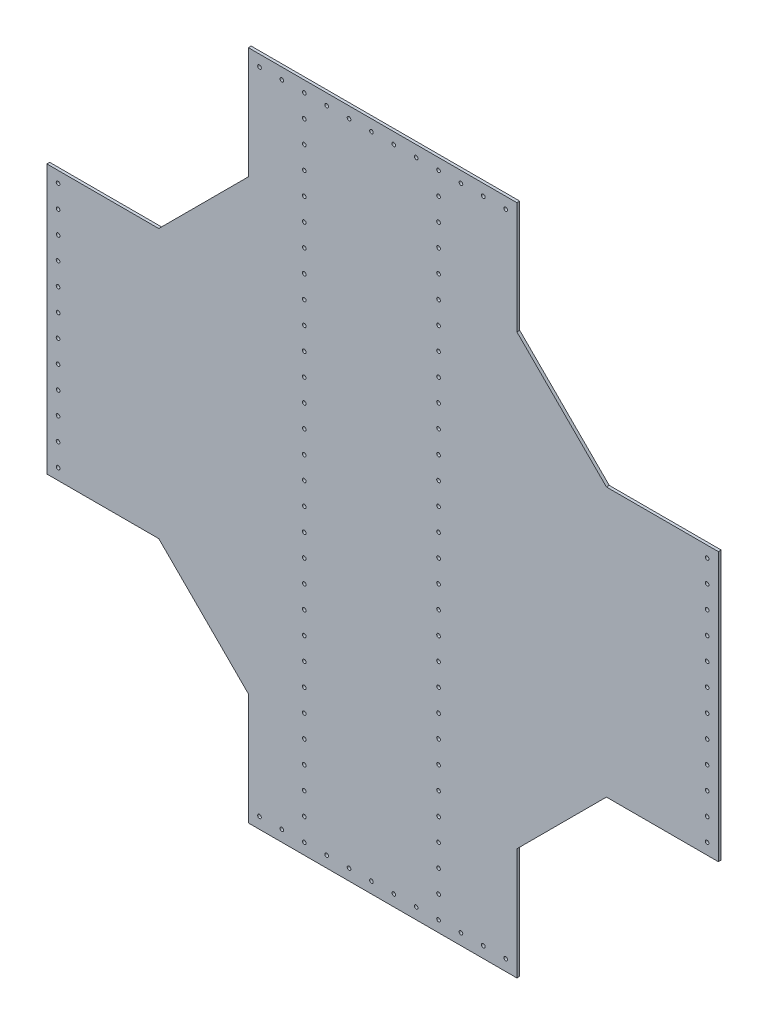
SolidWorks part; units mm, degrees
ref_plane "Front Plane" through (0, 0, 0) normal (0, 0, 1) x (1, 0, 0)
ref_plane "Top Plane" through (0, 0, 0) normal (0, 1, 0) x (1, 0, 0)
ref_plane "Right Plane" through (0, 0, 0) normal (1, 0, 0) x (0, 0, -1)
sketch "Sketch1" plane through (0, 0, 0) normal (0, 0, 1) x (1, 0, 0)
  line L0 (317.5, 38.1) -> (317.5, 749.3) construction
  line L1 (317.5, 546.1) -> (190.5, 546.1)
  line L2 (317.5, 546.1) -> (317.5, 241.3)
  line L3 (317.5, 241.3) -> (190.5, 241.3)
  line L4 (-444.5, 546.1) -> (-444.5, 241.3)
  line L5 (-444.5, 38.1) -> (-444.5, 749.3) construction
  line L7 (88.9, 774.7) -> (-215.9, 774.7)
  line L8 (88.9, 774.7) -> (88.9, 647.7)
  line L9 (88.9, 12.7) -> (-215.9, 12.7)
  line L10 (-215.9, 774.7) -> (-215.9, 647.7)
  line L11 (317.5, 12.7) -> (-444.5, 12.7) construction
  line L12 (190.5, 241.3) -> (88.9, 139.7)
  line L13 (317.5, 774.7) -> (-444.5, 774.7) construction
  line L14 (-63.5, 774.7) -> (-63.5, 12.7) construction
  line L15 (317.5, 393.7) -> (-444.5, 393.7) construction
  line L16 (190.5, 546.1) -> (88.9, 647.7)
  line L17 (-317.5, 241.3) -> (-215.9, 139.7)
  line L18 (-317.5, 546.1) -> (-215.9, 647.7)
  line L19 (88.9, 139.7) -> (88.9, 12.7)
  line L20 (-317.5, 546.1) -> (-444.5, 546.1)
  line L21 (-215.9, 139.7) -> (-215.9, 12.7)
  line L22 (-317.5, 241.3) -> (-444.5, 241.3)
  line L23 (76.2, 762) -> (50.8, 762) construction
  line L24 (-152.4, 25.4) -> (-152.4, 50.8) construction
  line L25 (0, 25.4) -> (0, 50.8) construction
  line L26 (-431.8, 533.4) -> (-431.8, 508) construction
  circle A0 centre (76.2, 762) radius 2.0701
  circle A1 centre (50.8, 762) radius 2.0701
  circle A2 centre (25.4, 762) radius 2.0701
  circle A3 centre (0, 762) radius 2.0701
  circle A4 centre (-25.4, 762) radius 2.0701
  circle A5 centre (-50.8, 762) radius 2.0701
  circle A6 centre (-76.2, 762) radius 2.0701
  circle A7 centre (-101.6, 762) radius 2.0701
  circle A8 centre (-127, 762) radius 2.0701
  circle A9 centre (-152.4, 762) radius 2.0701
  circle A10 centre (-177.8, 762) radius 2.0701
  circle A11 centre (-203.2, 762) radius 2.0701
  circle A12 centre (76.2, 25.4) radius 2.0701
  circle A13 centre (50.8, 25.4) radius 2.0701
  circle A14 centre (-50.8, 25.4) radius 2.0701
  circle A15 centre (-25.4, 25.4) radius 2.0701
  circle A16 centre (0, 25.4) radius 2.0701
  circle A17 centre (25.4, 25.4) radius 2.0701
  circle A18 centre (-76.2, 25.4) radius 2.0701
  circle A19 centre (-101.6, 25.4) radius 2.0701
  circle A20 centre (-127, 25.4) radius 2.0701
  circle A21 centre (-152.4, 25.4) radius 2.0701
  circle A22 centre (-177.8, 25.4) radius 2.0701
  circle A23 centre (-203.2, 25.4) radius 2.0701
  circle A24 centre (-152.4, 50.8) radius 2.0701
  circle A25 centre (-152.4, 76.2) radius 2.0701
  circle A26 centre (-152.4, 101.6) radius 2.0701
  circle A27 centre (-152.4, 127) radius 2.0701
  circle A28 centre (-152.4, 152.4) radius 2.0701
  circle A29 centre (-152.4, 177.8) radius 2.0701
  circle A30 centre (-152.4, 203.2) radius 2.0701
  circle A31 centre (-152.4, 228.6) radius 2.0701
  circle A32 centre (-152.4, 254) radius 2.0701
  circle A33 centre (-152.4, 279.4) radius 2.0701
  circle A34 centre (-152.4, 304.8) radius 2.0701
  circle A35 centre (-152.4, 330.2) radius 2.0701
  circle A36 centre (-152.4, 355.6) radius 2.0701
  circle A37 centre (-152.4, 381) radius 2.0701
  circle A38 centre (-152.4, 406.4) radius 2.0701
  circle A39 centre (-152.4, 431.8) radius 2.0701
  circle A40 centre (-152.4, 457.2) radius 2.0701
  circle A41 centre (-152.4, 482.6) radius 2.0701
  circle A42 centre (-152.4, 508) radius 2.0701
  circle A43 centre (-152.4, 533.4) radius 2.0701
  circle A44 centre (-152.4, 558.8) radius 2.0701
  circle A45 centre (-152.4, 584.2) radius 2.0701
  circle A46 centre (-152.4, 609.6) radius 2.0701
  circle A47 centre (-152.4, 635) radius 2.0701
  circle A48 centre (-152.4, 660.4) radius 2.0701
  circle A49 centre (-152.4, 685.8) radius 2.0701
  circle A50 centre (-152.4, 711.2) radius 2.0701
  circle A51 centre (-152.4, 736.6) radius 2.0701
  circle A52 centre (0, 50.8) radius 2.0701
  circle A53 centre (0, 76.2) radius 2.0701
  circle A54 centre (0, 101.6) radius 2.0701
  circle A55 centre (0, 127) radius 2.0701
  circle A56 centre (0, 152.4) radius 2.0701
  circle A57 centre (0, 177.8) radius 2.0701
  circle A58 centre (0, 203.2) radius 2.0701
  circle A59 centre (0, 228.6) radius 2.0701
  circle A60 centre (0, 254) radius 2.0701
  circle A61 centre (0, 279.4) radius 2.0701
  circle A62 centre (0, 304.8) radius 2.0701
  circle A63 centre (0, 330.2) radius 2.0701
  circle A64 centre (0, 355.6) radius 2.0701
  circle A65 centre (0, 381) radius 2.0701
  circle A66 centre (0, 406.4) radius 2.0701
  circle A67 centre (0, 431.8) radius 2.0701
  circle A68 centre (0, 457.2) radius 2.0701
  circle A69 centre (0, 482.6) radius 2.0701
  circle A70 centre (0, 508) radius 2.0701
  circle A71 centre (0, 533.4) radius 2.0701
  circle A72 centre (0, 558.8) radius 2.0701
  circle A73 centre (0, 584.2) radius 2.0701
  circle A74 centre (0, 609.6) radius 2.0701
  circle A75 centre (0, 635) radius 2.0701
  circle A76 centre (0, 660.4) radius 2.0701
  circle A77 centre (0, 685.8) radius 2.0701
  circle A78 centre (0, 711.2) radius 2.0701
  circle A79 centre (0, 736.6) radius 2.0701
  circle A80 centre (-431.8, 533.4) radius 2.0701
  circle A81 centre (-431.8, 508) radius 2.0701
  circle A82 centre (-431.8, 482.6) radius 2.0701
  circle A83 centre (-431.8, 457.2) radius 2.0701
  circle A84 centre (-431.8, 431.8) radius 2.0701
  circle A85 centre (-431.8, 406.4) radius 2.0701
  circle A86 centre (-431.8, 381) radius 2.0701
  circle A87 centre (-431.8, 355.6) radius 2.0701
  circle A88 centre (-431.8, 330.2) radius 2.0701
  circle A89 centre (-431.8, 304.8) radius 2.0701
  circle A90 centre (-431.8, 279.4) radius 2.0701
  circle A91 centre (-431.8, 254) radius 2.0701
  circle A92 centre (304.8, 254) radius 2.0701
  circle A93 centre (304.8, 279.4) radius 2.0701
  circle A94 centre (304.8, 304.8) radius 2.0701
  circle A95 centre (304.8, 330.2) radius 2.0701
  circle A96 centre (304.8, 355.6) radius 2.0701
  circle A97 centre (304.8, 381) radius 2.0701
  circle A98 centre (304.8, 406.4) radius 2.0701
  circle A99 centre (304.8, 431.8) radius 2.0701
  circle A100 centre (304.8, 457.2) radius 2.0701
  circle A101 centre (304.8, 482.6) radius 2.0701
  circle A102 centre (304.8, 508) radius 2.0701
  circle A103 centre (304.8, 533.4) radius 2.0701
  point P20 (88.9, 241.3)
  dimension "D8" = 4.1402
  dimension "D13" = 4.1402
  dimension "D1" = 304.8
  dimension "D2" = 228.6
  dimension "D3" = 228.6
  dimension "D4" = 45
  dimension "D5" = 101.6
  dimension "D7" = 25.4
  dimension "D10" = 25.4
  dimension "D12" = 25.4
  dimension "D15" = 25.4
  dimension "D6" = 12
  dimension "D9" = 29
  dimension "D11" = 29
  dimension "D14" = 12
extrude "Boss-Extrude1" add sketch "Sketch1" along normal blind 3.175
